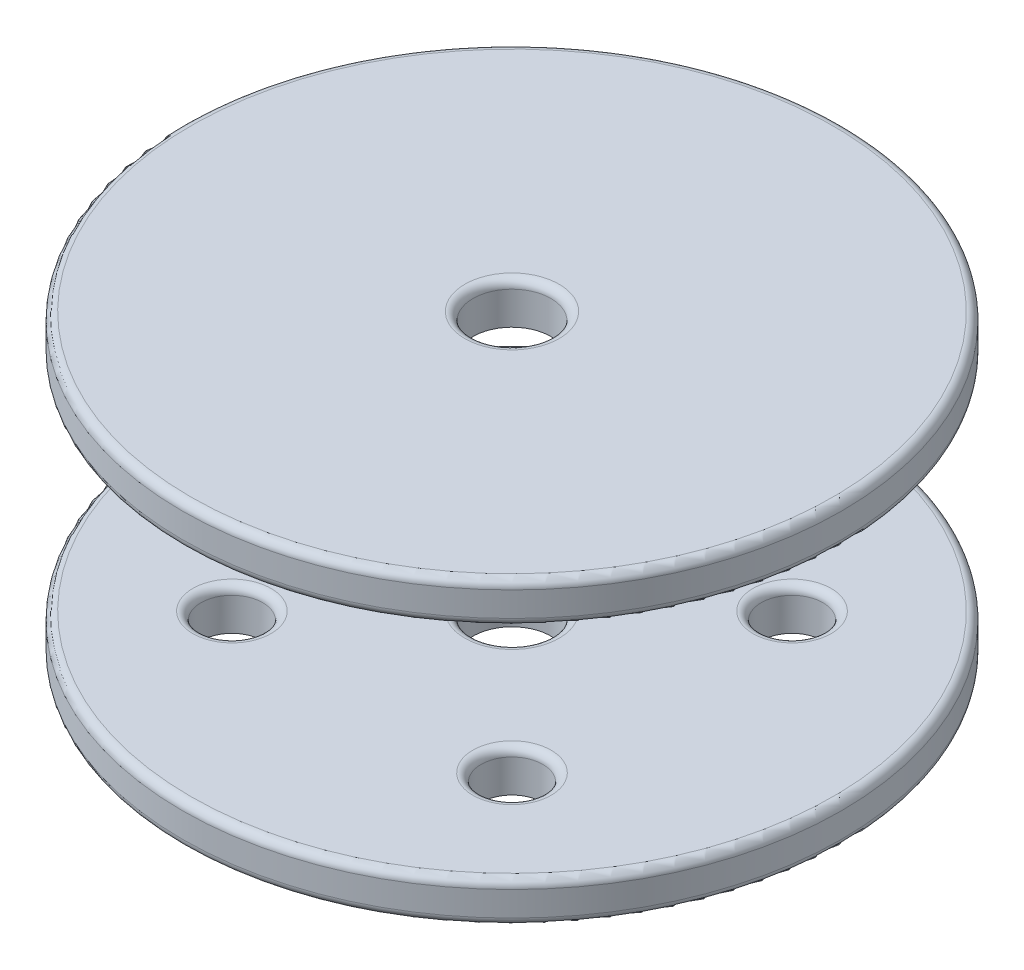
SolidWorks part; units mm, degrees
ref_plane "Front Plane" through (0, 0, 0) normal (0, 0, 1) x (1, 0, 0)
ref_plane "Top Plane" through (0, 0, 0) normal (0, 1, 0) x (1, 0, 0)
ref_plane "Right Plane" through (0, 0, 0) normal (1, 0, 0) x (0, 0, -1)
sketch "Sketch1" plane through (0, 0, 0) normal (0, 1, 0) x (1, 0, 0)
  line L0 (0, 0) -> (0, 50.8) construction
  line L1 (0, 50.8) -> (0, 0) construction
  line L2 (0, 0) -> (-50.8, 0) construction
  line L3 (-50.8, 0) -> (0, 0) construction
  line L4 (0, 0) -> (-35.921, 35.921) construction
  line L5 (-35.921, 35.921) -> (35.921, -35.921) construction
  line L6 (35.921, -35.921) -> (0, 0) construction
  line L7 (0, 0) -> (-35.921, -35.921) construction
  line L8 (-35.921, -35.921) -> (35.921, 35.921) construction
  circle A0 centre (0, 0) radius 50.8
  circle A1 centre (0, 0) radius 10.9844
  circle A2 centre (-37.7171, 37.7171) radius 5.8126
  circle A3 centre (37.7171, 37.7171) radius 5.8126
  circle A4 centre (37.7171, -37.7171) radius 5.8126
  circle A5 centre (-37.7171, -37.7171) radius 5.8126
  point P12 (0, 0)
  point P13 (0, 0)
  dimension "D1" = 53.34
  dimension "D2" = 101.6
extrude "Boss-Extrude1" add sketch "Sketch1" along normal blind 6.35 contours A0
sketch "Sketch2" plane through (0, 6.35, 0) normal (0, 1, 0) x (1, 0, 0)
  line L0 (0, 50.8) -> (0, 0) construction
  line L1 (0, 0) -> (-50.8, 0) construction
  circle A1 centre (-21.59, 21.59) radius 4.7625
  circle A2 centre (-21.59, -21.59) radius 4.7625
  circle A3 centre (21.59, -21.59) radius 4.7625
  circle A4 centre (21.59, 21.59) radius 4.7625
  circle A5 centre (0, 0) radius 6
  dimension "D1" = 21.59
  dimension "D2" = 21.59
extrude "Cut-Extrude1" cut sketch "Sketch2" against normal blind 6.35
fillet "Fillet1" radius 1.27 4 edges at (21.59, 6.35, -26.3525) (21.59, 6.35, 26.3525) (-21.59, 6.35, 16.8275) (-21.59, 6.35, -16.8275)
ref_plane "Plane2" through (0, 40, 0) normal (0, 1, 0) x (1, 0, 0)
sketch "Sketch4" plane through (0, 40, 0) normal (0, 1, 0) x (1, 0, 0)
  circle A0 centre (0, 0) radius 50.8
extrude "Boss-Extrude2" add sketch "Sketch4" along normal blind 6.35 separate body
sketch "Sketch5" plane through (0, 40, 0) normal (0, 1, 0) x (1, 0, 0)
  circle A0 centre (0, 0) radius 6
extrude "Cut-Extrude3" cut sketch "Sketch5" along normal blind 6.35
fillet "Fillet4" radius 1.27 1 edges at (0, 46.35, 6)
fillet "Fillet5" radius 1.27 1 edges at (0, 46.35, 50.8)
fillet "Fillet6" radius 1.27 1 edges at (0, 40, 50.8)
fillet "Fillet7" radius 1.27 1 edges at (0, 6.35, 50.8)
fillet "Fillet8" radius 1.27 1 edges at (0, 0, 50.8)
fillet "Fillet9" radius 1.27 1 edges at (0, 6.35, 6)
